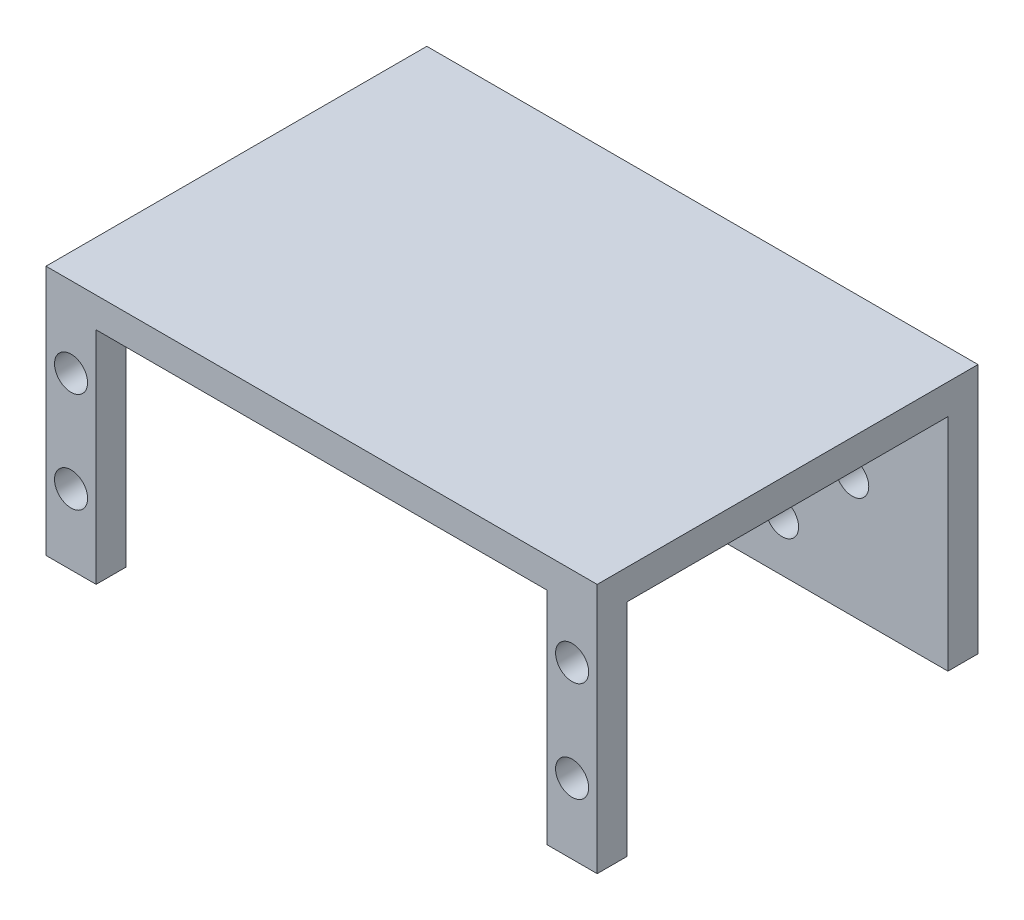
SolidWorks part; units mm, degrees
ref_plane "前视基准面" through (0, 0, 0) normal (0, 0, 1) x (1, 0, 0)
ref_plane "上视基准面" through (0, 0, 0) normal (0, 1, 0) x (1, 0, 0)
ref_plane "右视基准面" through (0, 0, 0) normal (1, 0, 0) x (0, 0, -1)
sketch "草图1" plane through (0, 0, 0) normal (0, 0, 1) x (1, 0, 0)
  line L1 (-27.5, -12.5) -> (27.5, -12.5)
  line L2 (-27.5, -12.5) -> (-27.5, 12.5)
  line L3 (-27.5, 12.5) -> (27.5, 12.5)
  line L4 (27.5, -12.5) -> (27.5, 12.5)
  line L5 (-27.5, -12.5) -> (27.5, 12.5) construction
  line L6 (-27.5, 12.5) -> (27.5, -12.5) construction
  point P0 (0, 0)
  dimension "D1" = 55
  dimension "D2" = 25
extrude "凸台-拉伸1" add sketch "草图1" along normal blind 3
sketch "草图2" plane through (0, 0, 3) normal (0, 0, 1) x (1, 0, 0)
  line L0 (27.5, -12.5) -> (27.5, 12.5) construction
  line L1 (-27.5, 12.5) -> (27.5, 12.5)
  line L2 (-27.5, 12.5) -> (-27.5, 9.5)
  line L3 (-27.5, 9.5) -> (27.5, 9.5)
  line L4 (27.5, 12.5) -> (27.5, 9.5)
  dimension "D1" = 3
extrude "凸台-拉伸2" add sketch "草图2" along normal blind 35
sketch "草图3" plane through (0, 9.5, 0) normal (0, -1, 0) x (1, 0, 0)
  line L1 (-27.5, 38) -> (-22.5, 38)
  line L2 (-27.5, 38) -> (-27.5, 35)
  line L3 (-27.5, 35) -> (-22.5, 35)
  line L4 (-22.5, 38) -> (-22.5, 35)
  line L5 (27.5, 38) -> (22.5, 38)
  line L6 (27.5, 38) -> (27.5, 35)
  line L7 (27.5, 35) -> (22.5, 35)
  line L8 (22.5, 38) -> (22.5, 35)
  dimension "D1" = 5
  dimension "D2" = 5
  dimension "D3" = 3
  dimension "D4" = 3
extrude "凸台-拉伸3" add sketch "草图3" along normal blind 22
sketch "草图4" plane through (0, 0, 38) normal (0, 0, 1) x (1, 0, 0)
  line L0 (-25, -12.5) -> (-25, 12.5) construction
  line L1 (-22.5, -12.5) -> (-27.5, -12.5) construction
  line L2 (27.5, 12.5) -> (-27.5, 12.5) construction
  line L3 (-22.5, 9.5) -> (22.5, 9.5) construction
  line L4 (0, 12.5) -> (0, 9.5) construction
  line L5 (-27.5, 9.5) -> (27.5, 9.5) construction
  circle A0 centre (-25, -5.5) radius 1.65
  circle A1 centre (-25, 4.5) radius 1.65
  circle A2 centre (25, 4.5) radius 1.65
  circle A3 centre (25, -5.5) radius 1.65
  dimension "D1" = 3.3
  dimension "D2" = 3.3
  dimension "D3" = 5
  dimension "D4" = 10
extrude "切除-拉伸1" cut sketch "草图4" against normal up to next
sketch "草图7" plane through (0, 0, 3) normal (0, 0, 1) x (1, 0, 0)
  line L0 (0, -0.5) -> (27.5, -0.5) construction
  line L1 (27.5, -12.5) -> (27.5, 12.5) construction
  line L2 (10.95, -12.5) -> (10.95, 12.5) construction
  line L3 (-27.5, -12.5) -> (27.5, -12.5) construction
  line L4 (27.5, 12.5) -> (-27.5, 12.5) construction
  circle A0 centre (17.95, -0.5) radius 1.65
  circle A1 centre (10.95, 6.5) radius 1.65
  circle A2 centre (3.95, -0.5) radius 1.65
  circle A3 centre (10.95, -7.5) radius 1.65
  dimension "D2" = 3.3
  dimension "D3" = 3.3
  dimension "D4" = 3.3
  dimension "D5" = 3.3
  dimension "D1" = 16.55
  dimension "D6" = 7
  dimension "D7" = 7
  dimension "D8" = 7
  dimension "D9" = 7
  dimension "D10" = 13
extrude "切除-拉伸2" cut sketch "草图7" against normal blind 20
